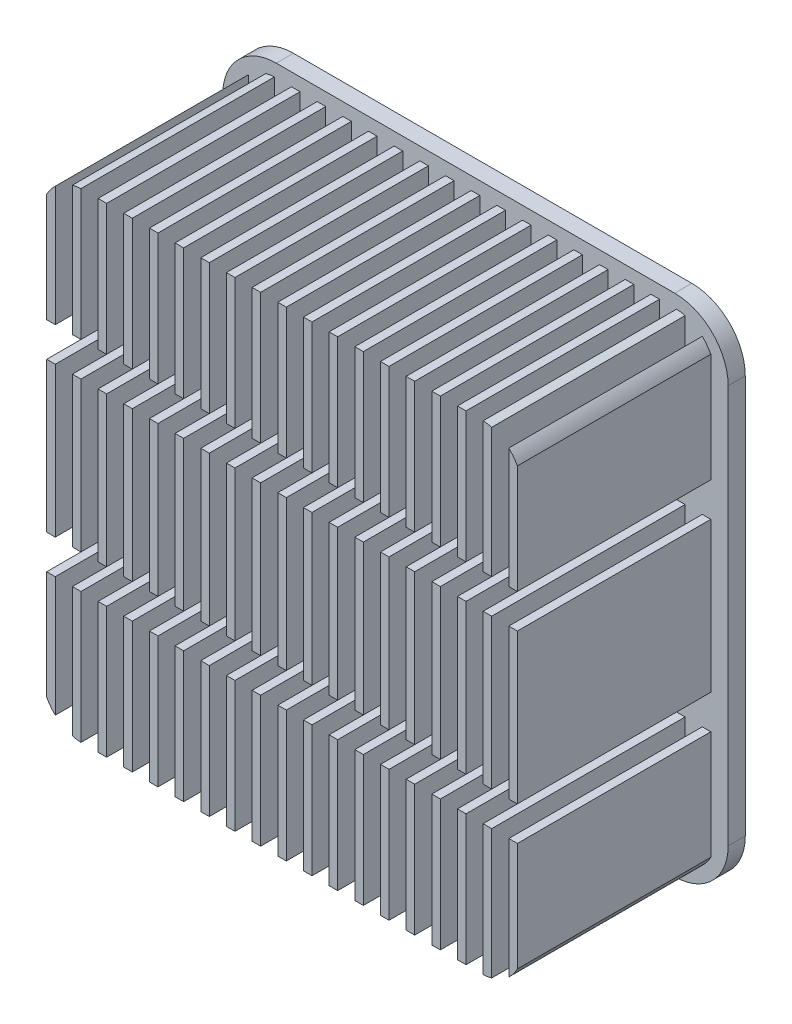
SolidWorks part; units mm, degrees
material "6061 Alloy"
ref_plane "Front Plane" through (0, 0, 0) normal (0, 0, 1) x (1, 0, 0)
ref_plane "Top Plane" through (0, 0, 0) normal (0, 1, 0) x (1, 0, 0)
ref_plane "Right Plane" through (0, 0, 0) normal (1, 0, 0) x (0, 0, -1)
sketch "Sketch1" plane through (0, 0, 0) normal (0, 0, 1) x (1, 0, 0)
  line L1 (-15, 15) -> (15, 15)
  line L2 (-15, 15) -> (-15, -15)
  line L3 (-15, -15) -> (15, -15)
  line L4 (15, 15) -> (15, -15)
  line L5 (-15, 15) -> (15, -15) construction
  line L6 (-15, -15) -> (15, 15) construction
  point P0 (0, 0)
  dimension "D1" = 30
ref_plane "Plane1" through (0, 0, 12.5) normal (0, 0, 1) x (1, 0, 0)
sketch "Sketch2" plane through (0, 0, 0) normal (0, 0, 1) x (1, 0, 0)
  line L0 (-15, 15) -> (-15, -15) construction
  line L1 (-15, -15) -> (15, -15) construction
  line L2 (15, 15) -> (15, -15) construction
  line L3 (-15, 15) -> (15, 15) construction
  line L4 (-15, 11.825) -> (-15, -11.825)
  line L5 (-11.825, -15) -> (11.825, -15)
  line L6 (15, 11.825) -> (15, -11.825)
  line L7 (-11.825, 15) -> (11.825, 15)
  arc A0 (-15, -11.825) -> (-11.825, -15) centre (-11.825, -11.825) ccw
  arc A1 (11.825, -15) -> (15, -11.825) centre (11.825, -11.825) ccw
  arc A2 (15, 11.825) -> (11.825, 15) centre (11.825, 11.825) ccw
  arc A3 (-15, 11.825) -> (-11.825, 15) centre (-11.825, 11.825) cw
  dimension "D1" = 3.175
extrude "Boss-Extrude1" add sketch "Sketch2" along normal blind 1.016
sketch "Sketch3" plane through (0, 0, 1.016) normal (0, 0, 1) x (1, 0, 0)
  line L0 (-15, 15) -> (15, -15) construction
  line L1 (-0.254, 14.5) -> (0.254, 14.5)
  line L2 (-0.254, 14.5) -> (-0.254, -14.5)
  line L3 (-0.254, -14.5) -> (0.254, -14.5)
  line L4 (0.254, 14.5) -> (0.254, -14.5)
  line L5 (-0.254, 14.5) -> (0.254, -14.5) construction
  line L6 (-0.254, -14.5) -> (0.254, 14.5) construction
  line L7 (1.27, 14.5) -> (1.778, 14.5)
  line L8 (1.27, -14.5) -> (1.778, -14.5)
  line L9 (1.27, 14.5) -> (1.27, -14.5)
  line L10 (1.778, 14.5) -> (1.778, -14.5)
  line L11 (2.794, 14.5) -> (3.302, 14.5)
  line L12 (2.794, -14.5) -> (3.302, -14.5)
  line L13 (2.794, 14.5) -> (2.794, -14.5)
  line L14 (3.302, 14.5) -> (3.302, -14.5)
  line L15 (4.318, 14.5) -> (4.826, 14.5)
  line L16 (4.318, -14.5) -> (4.826, -14.5)
  line L17 (4.318, 14.5) -> (4.318, -14.5)
  line L18 (4.826, 14.5) -> (4.826, -14.5)
  line L19 (5.842, 14.5) -> (6.35, 14.5)
  line L20 (5.842, -14.5) -> (6.35, -14.5)
  line L21 (5.842, 14.5) -> (5.842, -14.5)
  line L22 (6.35, 14.5) -> (6.35, -14.5)
  line L23 (7.366, 14.5) -> (7.874, 14.5)
  line L24 (7.366, -14.5) -> (7.874, -14.5)
  line L25 (7.366, 14.5) -> (7.366, -14.5)
  line L26 (7.874, 14.5) -> (7.874, -14.5)
  line L27 (8.89, 14.5) -> (9.398, 14.5)
  line L28 (8.89, -14.5) -> (9.398, -14.5)
  line L29 (8.89, 14.5) -> (8.89, -14.5)
  line L30 (9.398, 14.5) -> (9.398, -14.5)
  line L31 (10.414, 14.5) -> (10.922, 14.5)
  line L32 (10.414, -14.5) -> (10.922, -14.5)
  line L33 (10.414, 14.5) -> (10.414, -14.5)
  line L34 (10.922, 14.5) -> (10.922, -14.5)
  line L35 (11.938, 14.5) -> (12.446, 14.5)
  line L36 (11.938, -14.5) -> (12.446, -14.5)
  line L37 (11.938, 14.5) -> (11.938, -14.5)
  line L38 (12.446, 14.5) -> (12.446, -14.5)
  line L39 (13.462, 14.5) -> (13.97, 14.5)
  line L40 (13.462, -14.5) -> (13.97, -14.5)
  line L41 (13.462, 14.5) -> (13.462, -14.5)
  line L42 (13.97, 14.5) -> (13.97, -14.5)
  line L43 (-1.778, 14.5) -> (-1.27, 14.5)
  line L44 (-1.778, -14.5) -> (-1.27, -14.5)
  line L45 (-1.778, 14.5) -> (-1.778, -14.5)
  line L46 (-1.27, 14.5) -> (-1.27, -14.5)
  line L47 (-3.302, 14.5) -> (-2.794, 14.5)
  line L48 (-3.302, -14.5) -> (-2.794, -14.5)
  line L49 (-3.302, 14.5) -> (-3.302, -14.5)
  line L50 (-2.794, 14.5) -> (-2.794, -14.5)
  line L51 (-4.826, 14.5) -> (-4.318, 14.5)
  line L52 (-4.826, -14.5) -> (-4.318, -14.5)
  line L53 (-4.826, 14.5) -> (-4.826, -14.5)
  line L54 (-4.318, 14.5) -> (-4.318, -14.5)
  line L55 (-6.35, 14.5) -> (-5.842, 14.5)
  line L56 (-6.35, -14.5) -> (-5.842, -14.5)
  line L57 (-6.35, 14.5) -> (-6.35, -14.5)
  line L58 (-5.842, 14.5) -> (-5.842, -14.5)
  line L59 (-7.874, 14.5) -> (-7.366, 14.5)
  line L60 (-7.874, -14.5) -> (-7.366, -14.5)
  line L61 (-7.874, 14.5) -> (-7.874, -14.5)
  line L62 (-7.366, 14.5) -> (-7.366, -14.5)
  line L63 (-9.398, 14.5) -> (-8.89, 14.5)
  line L64 (-9.398, -14.5) -> (-8.89, -14.5)
  line L65 (-9.398, 14.5) -> (-9.398, -14.5)
  line L66 (-8.89, 14.5) -> (-8.89, -14.5)
  line L67 (-10.922, 14.5) -> (-10.414, 14.5)
  line L68 (-10.922, -14.5) -> (-10.414, -14.5)
  line L69 (-10.922, 14.5) -> (-10.922, -14.5)
  line L70 (-10.414, 14.5) -> (-10.414, -14.5)
  line L71 (-12.446, 14.5) -> (-11.938, 14.5)
  line L72 (-12.446, -14.5) -> (-11.938, -14.5)
  line L73 (-12.446, 14.5) -> (-12.446, -14.5)
  line L74 (-11.938, 14.5) -> (-11.938, -14.5)
  line L75 (-13.97, 14.5) -> (-13.462, 14.5)
  line L76 (-13.97, -14.5) -> (-13.462, -14.5)
  line L77 (-13.97, 14.5) -> (-13.97, -14.5)
  line L78 (-13.462, 14.5) -> (-13.462, -14.5)
  point P0 (0, 0)
  dimension "D1" = 29
  dimension "D2" = 0.508
  dimension "D3" = 10
  dimension "D4" = 10
extrude "Boss-Extrude2" add sketch "Sketch3" along normal up to surface (11.484 mm away) up to plane "Plane1"
sketch "Sketch5" plane through (0, 0, 12.5) normal (0, 0, 1) x (1, 0, 0)
  line L0 (-14.238, 11.825) -> (-14.238, -11.825)
  line L1 (-11.825, -14.238) -> (11.825, -14.238)
  line L2 (14.238, -11.825) -> (14.238, 11.825)
  line L3 (11.825, 14.238) -> (-11.825, 14.238)
  line L4 (-15, 11.825) -> (-15, -11.825)
  line L5 (11.825, 15) -> (-11.825, 15)
  line L6 (15, -11.825) -> (15, 11.825)
  line L7 (-11.825, -15) -> (11.825, -15)
  line L8 (-15, 11.825) -> (-15, -11.825) construction
  line L9 (11.825, 15) -> (-11.825, 15) construction
  line L10 (15, -11.825) -> (15, 11.825) construction
  line L11 (-11.825, -15) -> (11.825, -15) construction
  arc A0 (-14.238, -11.825) -> (-11.825, -14.238) centre (-11.825, -11.825) ccw
  arc A1 (11.825, -14.238) -> (14.238, -11.825) centre (11.825, -11.825) ccw
  arc A2 (14.238, 11.825) -> (11.825, 14.238) centre (11.825, 11.825) ccw
  arc A3 (-11.825, 14.238) -> (-14.238, 11.825) centre (-11.825, 11.825) ccw
  arc A4 (-15, -11.825) -> (-11.825, -15) centre (-11.825, -11.825) ccw
  arc A5 (-11.825, 15) -> (-15, 11.825) centre (-11.825, 11.825) ccw
  arc A6 (15, 11.825) -> (11.825, 15) centre (11.825, 11.825) ccw
  arc A7 (11.825, -15) -> (15, -11.825) centre (11.825, -11.825) ccw
  arc A8 (-15, -11.825) -> (-11.825, -15) centre (-11.825, -11.825) ccw construction
  arc A9 (-11.825, 15) -> (-15, 11.825) centre (-11.825, 11.825) ccw construction
  arc A10 (15, 11.825) -> (11.825, 15) centre (11.825, 11.825) ccw construction
  arc A11 (11.825, -15) -> (15, -11.825) centre (11.825, -11.825) ccw construction
  dimension "D1" = 0
  dimension "D2" = 0.762
extrude "Cut-Extrude1" cut sketch "Sketch5" against normal up to surface (11.484 mm away) flip side to cut up to face at (-12.192, 0, 1.016)
sketch "Sketch8" plane through (0, 0, 12.5) normal (0, 0, 1) x (1, 0, 0)
  line L0 (0, 0) -> (-20.2261, 0) construction
  line L1 (15.895, -4.445) -> (15.895, -6.477)
  line L2 (-16.3535, 4.445) -> (15.895, 4.445)
  line L3 (-16.3535, 4.445) -> (-16.3535, 6.477)
  line L4 (-16.3535, 6.477) -> (15.895, 6.477)
  line L5 (15.895, 4.445) -> (15.895, 6.477)
  line L6 (-16.3535, -4.445) -> (-16.3535, -6.477)
  line L7 (-16.3535, -4.445) -> (15.895, -4.445)
  line L8 (-16.3535, -6.477) -> (15.895, -6.477)
  dimension "D1" = 2.032
  dimension "D2" = 8.89
extrude "Cut-Extrude2" cut sketch "Sketch8" against normal up to surface (11.484 mm away) up to face at (-13.7306, 0, 1.016)
